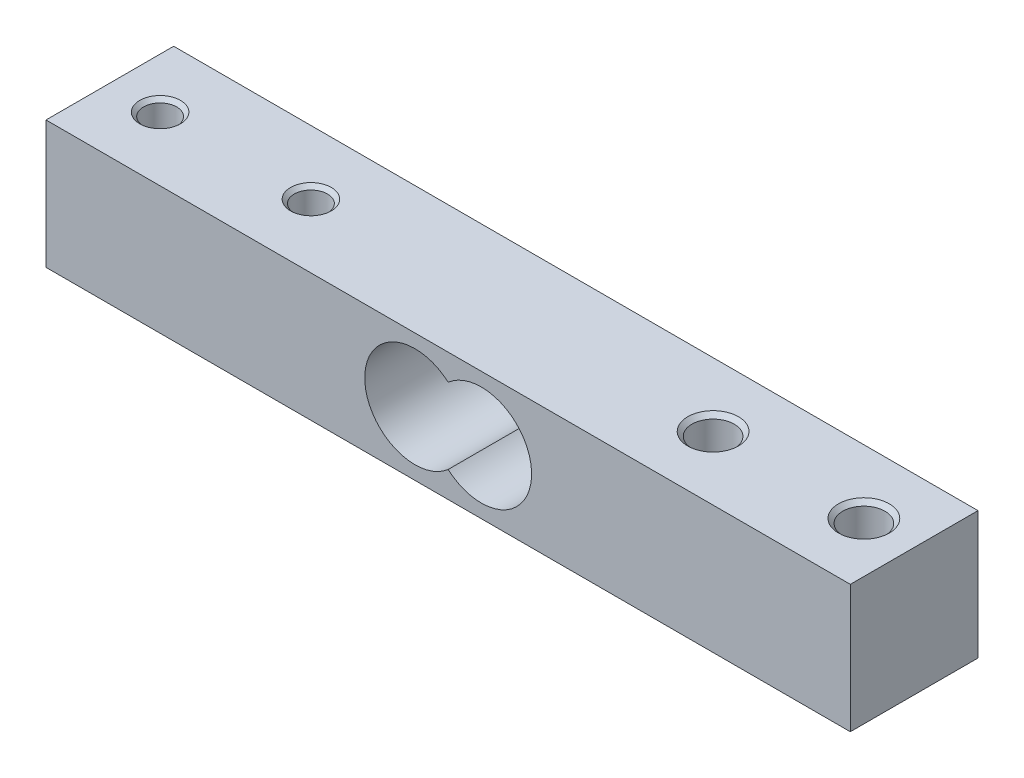
SolidWorks part; units mm, degrees
ref_plane "Front Plane" through (0, 0, 0) normal (0, 0, 1) x (1, 0, 0)
ref_plane "Top Plane" through (0, 0, 0) normal (0, 1, 0) x (1, 0, 0)
ref_plane "Right Plane" through (0, 0, 0) normal (1, 0, 0) x (0, 0, -1)
sketch "Sketch1" plane through (0, 0, 0) normal (0, 1, 0) x (1, 0, 0)
  line L1 (-40, -6.35) -> (40, -6.35)
  line L2 (-40, -6.35) -> (-40, 6.35)
  line L3 (-40, 6.35) -> (40, 6.35)
  line L4 (40, -6.35) -> (40, 6.35)
  line L5 (-40, -6.35) -> (40, 6.35) construction
  line L6 (-40, 6.35) -> (40, -6.35) construction
  point P0 (0, 0)
  dimension "D1" = 80
  dimension "D2" = 12.7
extrude "Boss-Extrude1" add sketch "Sketch1" along normal blind 12.7
sketch "Sketch4" plane through (0, 0, 6.35) normal (0, 0, 1) x (1, 0, 0)
  line L1 (0, 0) -> (0, 12.7) construction
  line L2 (-40, 12.7) -> (40, 12.7) construction
  arc A0 (0, 2.5937) -> (0, 10.1063) centre (3.3, 6.35) ccw
  arc A1 (0, 10.1063) -> (0, 2.5937) centre (-3.3, 6.35) ccw
  point P6 (0, 6.35)
  dimension "D2" = 10
  dimension "D1" = 3.3
extrude "Cut-Extrude1" cut sketch "Sketch4" against normal through all contours A0 A1
sketch "Sketch6" plane through (0, 12.7, 0) normal (0, 1, 0) x (1, 0, 0)
  line L0 (-40, 0) -> (-35, 0) construction
  line L1 (-40, 6.35) -> (-40, -6.35) construction
  line L2 (-124.0403, 0) -> (124.0403, 0) construction
  line L3 (-35, 0) -> (-20, 0) construction
  line L5 (0, -6.985) -> (0, 6.985) construction
  line L6 (35, 0) -> (20, 0) construction
  line L7 (40, 0) -> (35, 0) construction
  dimension "D1" = 5
  dimension "D2" = 20
sketch "Sketch14" plane through (0, 12.7, 0) normal (0, 1, 0) x (1, 0, 0)
  point P0 (-35, 0)
  point P3 (-20, 0)
hole_wizard "M4 Tapped Hole2" positions "Sketch14" profile "Sketch13" tap size "M4" standard "ISO" end condition through all
sketch "Sketch13" plane through (-35, 12.7, 0) normal (1, 0, 0) x (0, 0, 1)
  line L0 (0, 0) -> (0, 12.7)
  line L1 (0, 12.7) -> (1.65, 12.7)
  line L2 (1.65, 12.7) -> (1.65, 0.375)
  line L3 (1.65, 0.375) -> (2.025, 0)
  line L5 (2.025, 0) -> (0, 0)
  line L6 (-1.65, 0.375) -> (-2.025, 0) construction
  line L11 (0, -6.35) -> (0, 107.95) construction
  dimension "Thru Tap Drill Dia." = 3.3
  dimension "Thru Tap Drill Depth" = 12.7
  dimension "Near C'Sink Dia." = 4.05
  dimension "Near C'Sink Angle" = 90
cosmetic thread "Hole Thread5" parameters "D2"=4
cosmetic thread "Hole Thread6" parameters "D2"=4
sketch "Sketch17" plane through (0, 12.7, 0) normal (0, 1, 0) x (1, 0, 0)
  point P0 (35, 0)
  point P3 (20, 0)
hole_wizard "M5 Tapped Hole1" positions "Sketch17" profile "Sketch16" tap size "M5" standard "ISO" end condition through all
sketch "Sketch16" plane through (35, 12.7, 0) normal (1, 0, 0) x (0, 0, 1)
  line L0 (0, 0) -> (0, 12.7)
  line L1 (0, 12.7) -> (2.1, 12.7)
  line L2 (2.1, 12.7) -> (2.1, 0.425)
  line L3 (2.1, 0.425) -> (2.525, 0)
  line L5 (2.525, 0) -> (0, 0)
  line L6 (-2.1, 0.425) -> (-2.525, 0) construction
  line L11 (0, -6.35) -> (0, 16.4902) construction
  dimension "Thru Tap Drill Dia." = 4.2
  dimension "Thru Tap Drill Depth" = 12.7
  dimension "Near C'Sink Dia." = 5.05
  dimension "Near C'Sink Angle" = 90
cosmetic thread "Hole Thread7" parameters "D2"=5
cosmetic thread "Hole Thread8" parameters "D2"=5
equation "\"e\"= 3.3"
equation "\"D1@Sketch4\"=\"e\""
equation "\"d\"=10"
equation "\"D2@Sketch4\"=\"d\""
